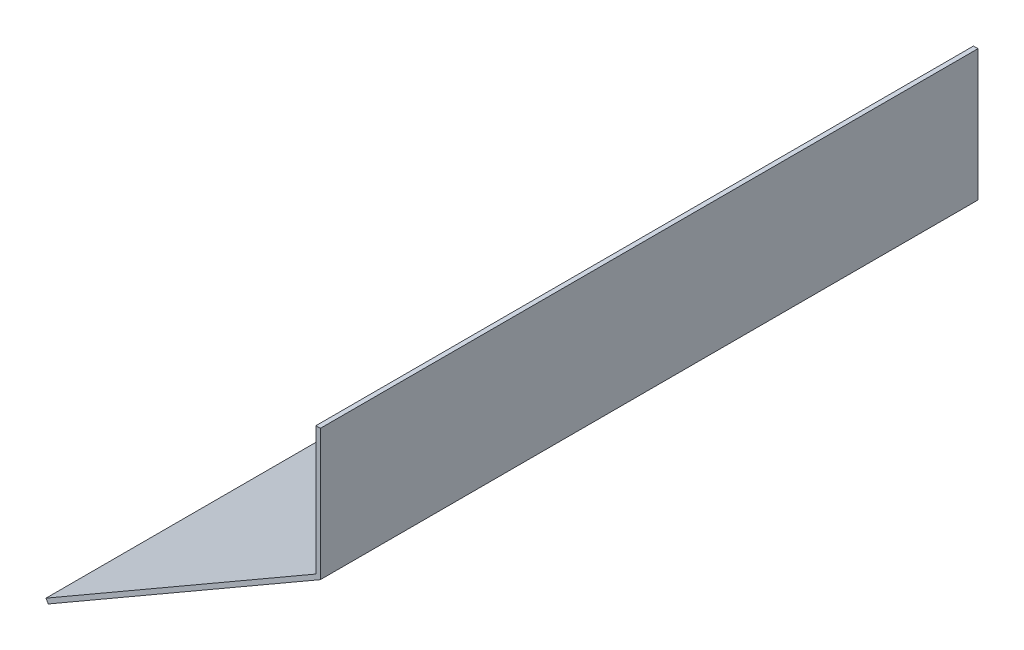
SolidWorks part; units mm, degrees
ref_plane "Front Plane" through (0, 0, 0) normal (0, 0, 1) x (1, 0, 0)
ref_plane "Top Plane" through (0, 0, 0) normal (0, 1, 0) x (1, 0, 0)
ref_plane "Right Plane" through (0, 0, 0) normal (1, 0, 0) x (0, 0, -1)
sketch "Sketch1" plane through (0, 0, 0) normal (0, 0, 1) x (1, 0, 0)
  line L0 (-65.7168, -44.4027) -> (53.2832, 24.302)
  line L1 (53.2832, 24.302) -> (53.2832, 80.9545)
  line L2 (-64.7168, -46.1347) -> (55.2832, 23.1473)
  line L3 (55.2832, 23.1473) -> (55.2832, 80.9545)
  line L4 (-64.7168, -46.1347) -> (-65.7168, -44.4027)
  line L5 (53.2832, 80.9545) -> (55.2832, 80.9545)
  dimension "D2" = 60
  dimension "D3" = 120
  dimension "D1" = 2
extrude "Boss-Extrude1" add sketch "Sketch1" along normal blind 290
